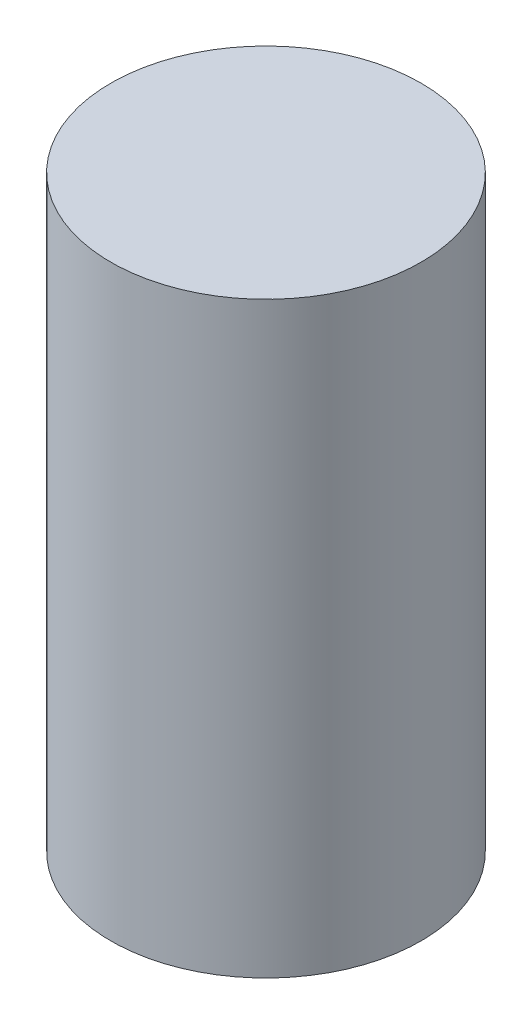
SolidWorks part; units mm, degrees
material "ABS"
ref_plane "Front Plane" through (0, 0, 0) normal (0, 0, 1) x (1, 0, 0)
ref_plane "Top Plane" through (0, 0, 0) normal (0, 1, 0) x (1, 0, 0)
ref_plane "Right Plane" through (0, 0, 0) normal (1, 0, 0) x (0, 0, -1)
sketch "Sketch1" plane through (0, 0, 0) normal (0, 1, 0) x (1, 0, 0)
  circle A0 centre (0, 0) radius 6.5024
  dimension "D1" = 13.0048
extrude "Boss-Extrude1" add sketch "Sketch1" along normal blind 24.638
